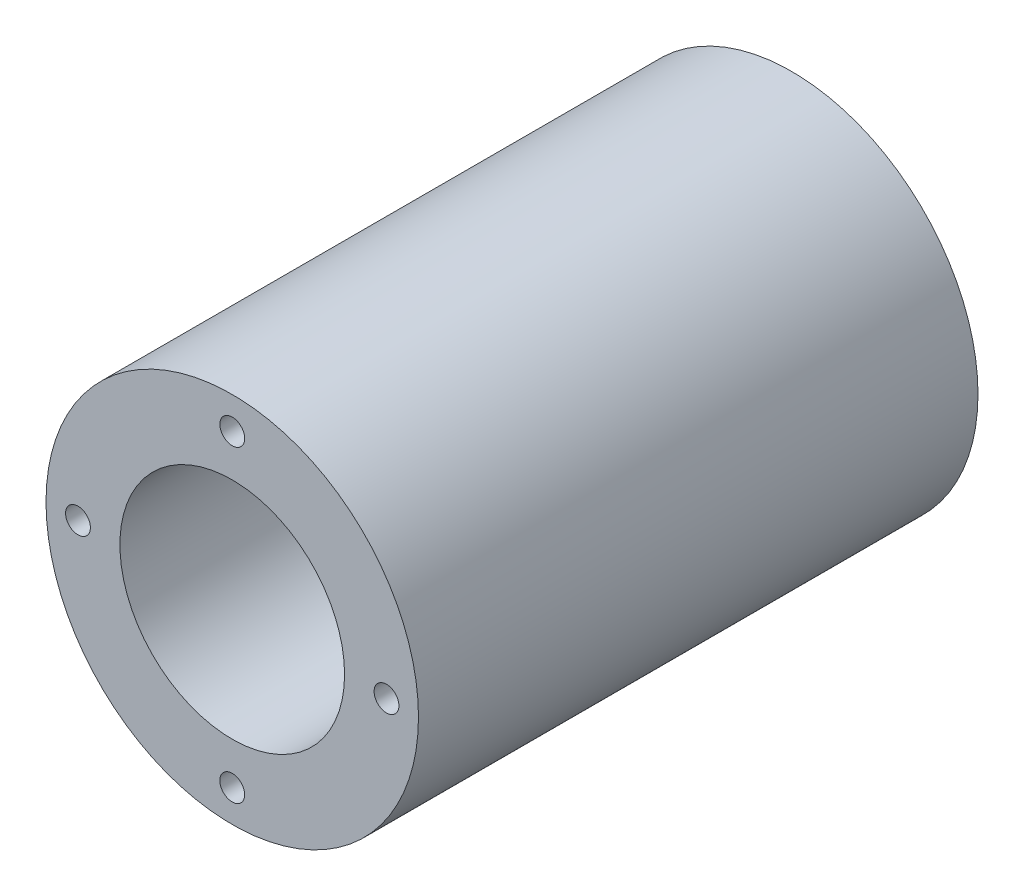
SolidWorks part; units mm, degrees
material "6061-T6 (SS)"
ref_plane "Front Plane" through (0, 0, 0) normal (0, 0, 1) x (1, 0, 0)
ref_plane "Top Plane" through (0, 0, 0) normal (0, 1, 0) x (1, 0, 0)
ref_plane "Right Plane" through (0, 0, 0) normal (1, 0, 0) x (0, 0, -1)
sketch "Sketch Spindle Skeleton" plane through (0, 0, 0) normal (1, 0, 0) x (0, 0, -1)
  line L0 (-108, -9.5) -> (-149, -9.5)
  line L5 (-1000, 0) -> (49000, 0)
  line L6 (0, -9.5) -> (0, 9.5)
  line L13 (0, 9.5) -> (-46.4, 9.5)
  line L26 (-46.4, 9.5) -> (-46.4, 14)
  line L27 (-46.4, 14) -> (-108, 14)
  line L32 (-108, 14) -> (-108, 9.5)
  line L34 (-165, 7) -> (-165, -7)
  line L36 (-108, -9.5) -> (-108, -14)
  line L37 (-108, -14) -> (-46.4, -14)
  line L38 (-46.4, -14) -> (-46.4, -9.5)
  line L39 (0, -9.5) -> (-46.4, -9.5)
  line L40 (-22.625, 37.5) -> (-14.625, 37.5)
  line L41 (-124.6, 22.6187) -> (-108, 22.6187)
  line L42 (-124.6, 22.6187) -> (-124.6, -22.6187)
  line L43 (-124.6, -22.6187) -> (-108, -22.6187)
  line L44 (-108, 22.6187) -> (-108, -22.6187)
  line L45 (-124.6, 22.6187) -> (-108, -22.6187) construction
  line L46 (-124.6, -22.6187) -> (-108, 22.6187) construction
  line L47 (-29.8, 22.6187) -> (-46.4, 22.6187)
  line L48 (-29.8, 22.6187) -> (-29.8, -22.6187)
  line L49 (-29.8, -22.6187) -> (-46.4, -22.6187)
  line L50 (-46.4, 22.6187) -> (-46.4, -22.6187)
  line L51 (-29.8, 22.6187) -> (-46.4, -22.6187) construction
  line L52 (-29.8, -22.6187) -> (-46.4, 22.6187) construction
  line L59 (-14.625, 37.5) -> (-14.625, -37.5)
  line L60 (-14.625, -37.5) -> (-22.625, -37.5)
  line L61 (-22.625, -22.6187) -> (-26.625, -22.6187)
  line L62 (-26.625, -22.6187) -> (-26.625, -12.5)
  line L63 (-26.625, -12.5) -> (-22.625, -12.5)
  line L64 (-22.625, -12.5) -> (-22.625, 12.5)
  line L65 (-22.625, 12.5) -> (-26.625, 12.5)
  line L66 (-26.625, 12.5) -> (-26.625, 22.6187)
  line L67 (-26.625, 22.6187) -> (-22.625, 22.6187)
  line L68 (-22.625, 22.6187) -> (-22.625, 37.5)
  line L69 (-22.625, -22.6187) -> (-22.625, -37.5)
  line L71 (-136.284, 37.5) -> (-23.625, 37.5)
  line L72 (-136.284, 37.5) -> (-136.284, -37.5)
  line L73 (-136.284, -37.5) -> (-23.625, -37.5)
  line L74 (-23.625, 37.5) -> (-23.625, -37.5)
  line L75 (-136.284, 37.5) -> (-23.625, -37.5) construction
  line L76 (-136.284, -37.5) -> (-23.625, 37.5) construction
  line L77 (-149, -9.5) -> (-149, -7)
  line L78 (-149, -7) -> (-165, -7)
  line L79 (-108, 9.5) -> (-149, 9.5)
  line L80 (-149, 7) -> (-165, 7)
  line L81 (-149, 9.5) -> (-149, 7)
  line L82 (-128.5, 9.5) -> (-128.5, -9.5) construction
  line L83 (-23.2, 9.5) -> (-23.2, -9.5) construction
  line L96 (-136.284, 37.5) -> (-144.284, 37.5)
  line L98 (-136.284, -37.5) -> (-144.284, -37.5)
  line L99 (-144.284, 37.5) -> (-144.284, -37.5)
  line L110 (-136.284, 37.5) -> (-136.284, -37.5)
  point P3 (0, 0)
  point P18 (-116.3, 0)
  point P24 (-38.1, 0)
  point P29 (-79.9545, 0)
  point P48 (-14.625, 31.0593)
  point P70 (-144.284, 31.0593)
sketch "Sketch1" plane through (0, 0, 0) normal (1, 0, 0) x (0, 0, -1)
  line L0 (-23.625, 37.5) -> (-23.625, -37.5) construction
  line L1 (-136.284, -37.5) -> (-23.625, -37.5) construction
  line L2 (-136.284, 37.5) -> (-136.284, -37.5) construction
  line L3 (-136.284, 37.5) -> (-23.625, 37.5) construction
  line L4 (-23.625, 37.5) -> (-23.625, -37.5)
  line L5 (-136.284, -37.5) -> (-23.625, -37.5)
  line L6 (-136.284, 37.5) -> (-136.284, -37.5)
  line L7 (-136.284, 37.5) -> (-23.625, 37.5)
  line L8 (-26.625, 22.6187) -> (-22.625, 22.6187) construction
  line L10 (-136.284, 22.6187) -> (-23.625, 22.6187)
  line L15 (-136.284, 0) -> (-23.625, 0) construction
revolve "Revolve1" add sketch "Sketch1" angle 360 about L15
sketch "Back Hole Top Location" plane through (0, 0, 23.625) normal (0, 0, -1) x (-1, 0, 0)
  point P9 (0, 31.0593)
hole_wizard "M6x1.0 Tapped Hole3" positions "Sketch8" profile "Sketch9" tap size "M6x1.0" standard "ANSI Metric"
sketch "Sketch8" plane through (0, 0, 23.625) normal (0, 0, -1) x (-1, 0, 0)
  point P0 (0, 31.0593)
sketch "Sketch9" plane through (0, 31.0593, 23.625) normal (1, 0, 0) x (0, 1, 0)
  line L0 (0, 0) -> (0, 16.5022)
  line L1 (0, 16.5022) -> (2.5, 15)
  line L2 (2.5, 15) -> (2.5, 0)
  line L5 (2.5, 0) -> (0, 0)
  line L10 (0, 16.5022) -> (-2.5, 15) construction
  line L11 (0, -6.35) -> (0, 107.95) construction
  dimension "Tap Drill Dia." = 5
  dimension "Tap Drill Depth" = 15
  dimension "Drill Angle" = 118
pattern_circular "BackFacePattern" count 6 over 360 about axis through (0, 0, 0) along (0, 0, 1) of "M6x1.0 Tapped Hole3"
ref_plane "Midplane" through (0, 0, 79.9545) normal (0, 0, -1) x (-1, 0, 0)
sketch "Front Hole Top Location" plane through (0, 0, 136.284) normal (0, 0, 1) x (1, 0, 0)
  point P0 (0, 31.0593)
hole_wizard "M6x1.0 Tapped Hole2" positions "Sketch5" profile "Sketch6" tap size "M6x1.0" standard "ANSI Metric"
sketch "Sketch5" plane through (0, 0, 136.284) normal (0, 0, 1) x (1, 0, 0)
  point P0 (0, 31.0593)
sketch "Sketch6" plane through (0, 31.0593, 136.284) normal (1, 0, 0) x (0, -1, 0)
  line L0 (0, 0) -> (0, 16.5022)
  line L1 (0, 16.5022) -> (2.5, 15)
  line L2 (2.5, 15) -> (2.5, 0)
  line L5 (2.5, 0) -> (0, 0)
  line L10 (0, 16.5022) -> (-2.5, 15) construction
  line L11 (0, -6.35) -> (0, 107.95) construction
  dimension "Tap Drill Dia." = 5
  dimension "Tap Drill Depth" = 15
  dimension "Drill Angle" = 118
pattern_circular "FrontFacePattern" count 4 over 360 about axis through (0, 0, 0) along (0, 0, 1) of "M6x1.0 Tapped Hole2"
sketch "Sketch7" plane through (0, 0, 23.625) normal (0, 0, -1) x (-1, 0, 0)
  circle A0 centre (0, 0) radius 26.9875
  circle A1 centre (0, 0) radius 25.4
  dimension "D1" = 53.975
  dimension "D2" = 50.8
extrude "Cut-Extrude1" cut sketch "Sketch7" against normal blind 0.5
